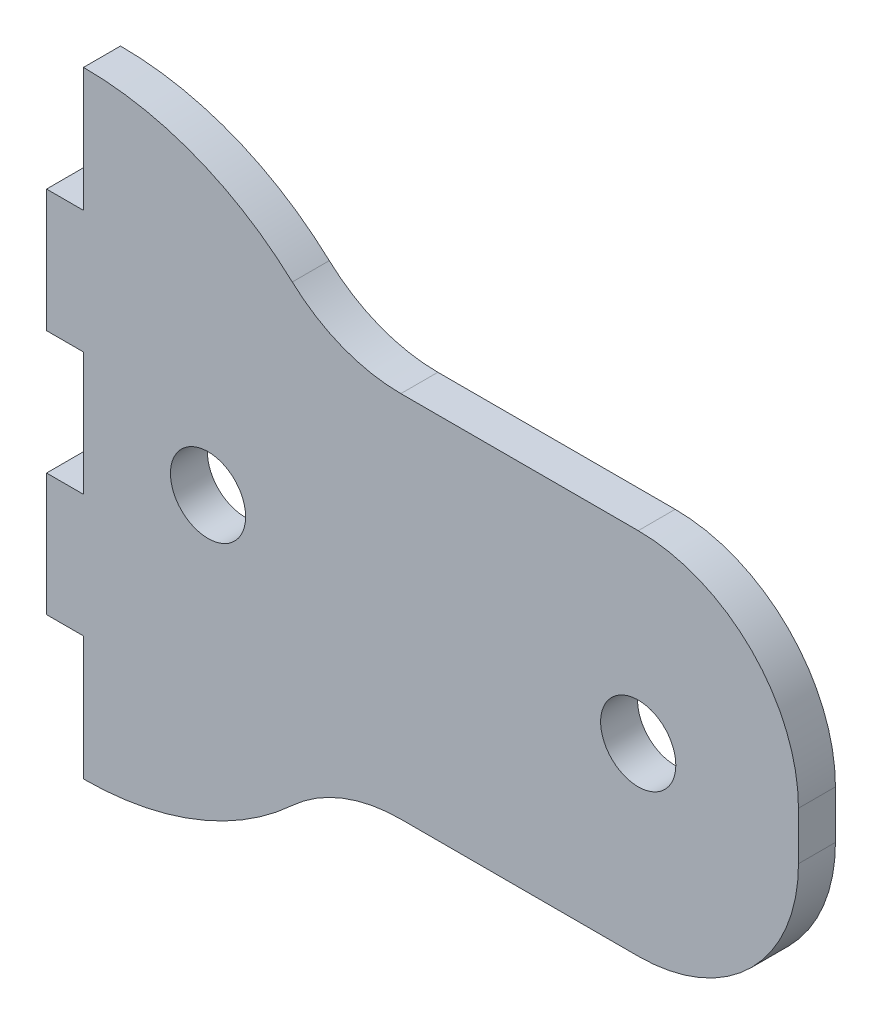
SolidWorks part; units mm, degrees
ref_plane "Front Plane" through (0, 0, 0) normal (0, 0, 1) x (1, 0, 0)
ref_plane "Top Plane" through (0, 0, 0) normal (0, 1, 0) x (1, 0, 0)
ref_plane "Right Plane" through (0, 0, 0) normal (1, 0, 0) x (0, 0, -1)
sketch "Sketch1" plane through (0, 0, 0) normal (0, 0, 1) x (1, 0, 0)
  line L0 (0, 25) -> (0, -25) construction
  line L1 (-25, -25) -> (25, -25) construction
  line L2 (-25, -25) -> (-25, 25) construction
  line L3 (-25, 25) -> (25, 25) construction
  line L4 (25, -25) -> (25, 25) construction
  line L5 (-25, -25) -> (25, 25) construction
  line L6 (-25, 25) -> (25, -25) construction
  line L7 (0, 25) -> (0, 14.95)
  line L8 (0, 14.95) -> (-3, 14.95)
  line L9 (-3, 14.95) -> (-3, 5)
  line L10 (-3, 5) -> (0, 5)
  line L11 (0, 5) -> (0, -5)
  line L12 (0, 0) -> (25, 0) construction
  line L13 (-3, -5) -> (0, -5)
  line L14 (-3, -14.95) -> (-3, -5)
  line L15 (0, -14.95) -> (-3, -14.95)
  line L16 (0, -25) -> (0, -14.95)
  line L17 (0, 25) -> (0, -25) construction
  line L18 (58, 25) -> (58, -25) construction
  line L19 (0, 14.95) -> (58, 14.95) construction
  line L20 (0, -14.95) -> (58, -14.95) construction
  line L21 (25.7449, 14.95) -> (45, 14.95)
  line L22 (58, 1.95) -> (58, -1.95)
  line L23 (45, -14.95) -> (25.7449, -14.95)
  arc A0 (0, -25) -> (16.9374, -18.3882) centre (0, 0) ccw
  arc A1 (16.9374, 18.3882) -> (0, 25) centre (0, 0) ccw
  arc A2 (58, -1.95) -> (45, -14.95) centre (45, -1.95) cw
  arc A3 (45, 14.95) -> (58, 1.95) centre (45, 1.95) cw
  arc A4 (25.7449, 14.95) -> (16.9374, 18.3882) centre (25.7449, 27.95) cw
  arc A5 (25.7449, -14.95) -> (16.9374, -18.3882) centre (25.7449, -27.95) ccw
  point P0 (0, 0)
  point P32 (20.0374, 14.95)
  point P35 (20.0374, -14.95)
  dimension "D6" = 13
  dimension "D1" = 5
  dimension "D2" = 9.95
  dimension "D3" = 3
  dimension "D4" = 50
  dimension "D5" = 58
extrude "Boss-Extrude1" add sketch "Sketch1" along normal blind 3
hole_wizard "Ø6.1 (6.1) Diameter Hole1" positions "Sketch3" profile "Sketch2" hole size "Ø6.1" standard "DIN"
sketch "Sketch3" plane through (0, 0, 3) normal (0, 0, 1) x (1, 0, 0)
  line L2 (0, 5) -> (0, -5) construction
  line L3 (58, 0) -> (0, 0) construction
  line L4 (58, -1.95) -> (58, 1.95) construction
  point P0 (10.1, 0)
  point P24 (45, 0)
  dimension "D1" = 10.1
  dimension "D2" = 45
sketch "Sketch2" plane through (10.1, 0, 3) normal (1, 0, 0) x (0, -1, 0)
  line L0 (0, 0) -> (0, 11.8326)
  line L1 (0, 11.8326) -> (3.05, 10)
  line L2 (3.05, 10) -> (3.05, 0)
  line L5 (3.05, 0) -> (0, 0)
  line L10 (0, 11.8326) -> (-3.05, 10) construction
  line L11 (0, -6.35) -> (0, 107.95) construction
  dimension "Hole Dia." = 6.1
  dimension "Hole Depth" = 10
  dimension "Drill Angle" = 118
